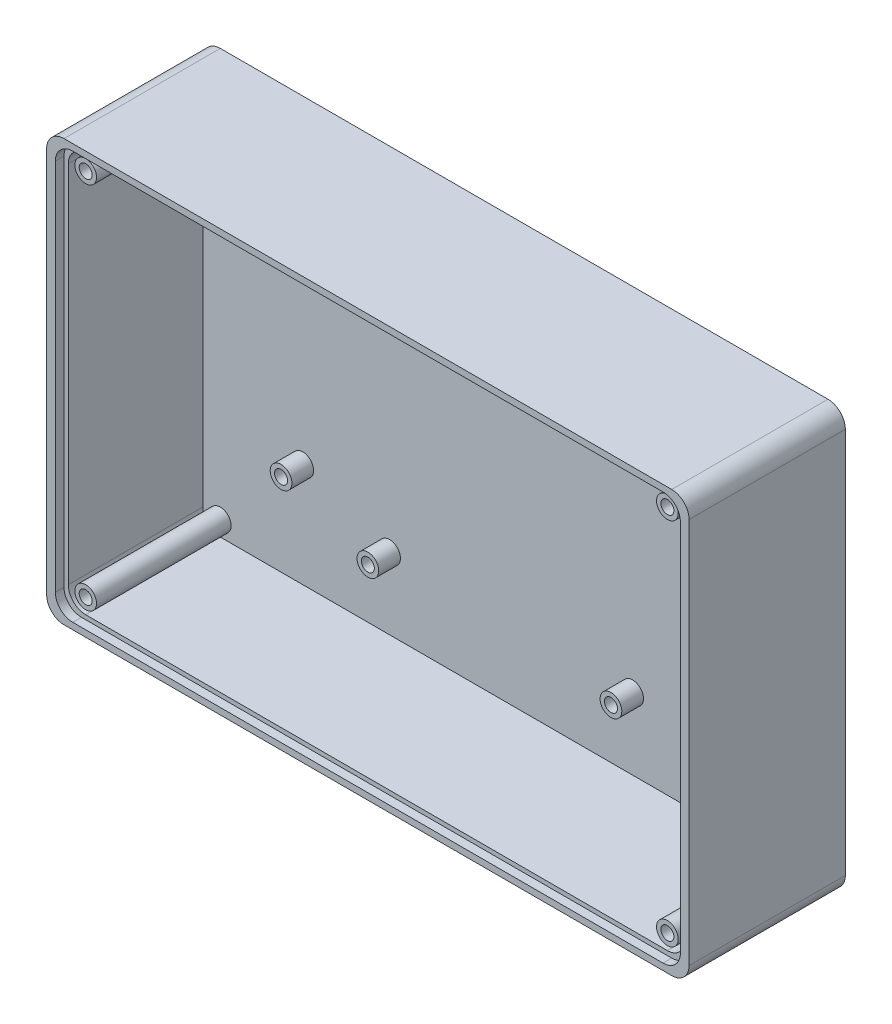
SolidWorks part; units mm, degrees
material "ABS"
ref_plane "Plano frontal" through (0, 0, 0) normal (0, 0, 1) x (1, 0, 0)
ref_plane "Plano superior" through (0, 0, 0) normal (0, 1, 0) x (1, 0, 0)
ref_plane "Plano direito" through (0, 0, 0) normal (1, 0, 0) x (0, 0, -1)
sketch "Esboço1" plane through (0, 0, 0) normal (0, 0, 1) x (1, 0, 0)
  line L1 (-70, -48.5) -> (70, -48.5)
  line L2 (-74, -44.5) -> (-74, 44.5)
  line L3 (-70, 48.5) -> (70, 48.5)
  line L4 (74, -44.5) -> (74, 44.5)
  line L5 (-74, -48.5) -> (74, 48.5) construction
  line L6 (-74, 48.5) -> (74, -48.5) construction
  arc A0 (70, -48.5) -> (74, -44.5) centre (70, -44.5) ccw
  arc A1 (70, 48.5) -> (74, 44.5) centre (70, 44.5) cw
  arc A2 (-74, 44.5) -> (-70, 48.5) centre (-70, 44.5) cw
  arc A3 (-70, -48.5) -> (-74, -44.5) centre (-70, -44.5) cw
  point P0 (0, 0)
  dimension "D3" = 4
  dimension "D1" = 148
  dimension "D2" = 97
extrude "Ressalto-extrusão1" add sketch "Esboço1" along normal mid plane 36
sketch "Esboço2" plane through (0, 0, 18) normal (0, 0, 1) x (1, 0, 0)
  line L1 (-68, -47) -> (68, -47)
  line L2 (-72, -43) -> (-72, 43)
  line L3 (-68, 47) -> (68, 47)
  line L4 (72, -43) -> (72, 43)
  line L5 (-72, -47) -> (72, 47) construction
  line L6 (-72, 47) -> (72, -47) construction
  arc A0 (68, 47) -> (72, 43) centre (68, 43) cw
  arc A1 (68, -47) -> (72, -43) centre (68, -43) ccw
  arc A2 (-68, -47) -> (-72, -43) centre (-68, -43) cw
  arc A3 (-72, 43) -> (-68, 47) centre (-68, 43) cw
  point P0 (0, 0)
  dimension "D3" = 4
  dimension "D1" = 94
  dimension "D2" = 144
extrude "Corte-extrusão1" cut sketch "Esboço2" against normal blind 2
sketch "Esboço3" plane through (0, 0, 16) normal (0, 0, 1) x (1, 0, 0)
  line L1 (-67, -46) -> (67, -46)
  line L2 (-71, -42) -> (-71, 42)
  line L3 (-67, 46) -> (67, 46)
  line L4 (71, -42) -> (71, 42)
  line L5 (-71, -46) -> (71, 46) construction
  line L6 (-71, 46) -> (71, -46) construction
  arc A0 (67, 46) -> (71, 42) centre (67, 42) cw
  arc A1 (67, -46) -> (71, -42) centre (67, -42) ccw
  arc A2 (-67, -46) -> (-71, -42) centre (-67, -42) cw
  arc A3 (-71, 42) -> (-67, 46) centre (-67, 42) cw
  point P0 (0, 0)
  dimension "D3" = 4
  dimension "D1" = 92
  dimension "D2" = 142
extrude "Corte-extrusão2" cut sketch "Esboço3" against normal blind 31
sketch "Esboço4" plane through (0, 0, -15) normal (0, 0, 1) x (1, 0, 0)
  line L0 (0, 0) -> (0, 58.4617) construction
  line L1 (0, 0) -> (89.051, 0) construction
  circle A0 centre (-28, 29.5) radius 1.5
  circle A1 centre (28, 29.5) radius 1.5
  circle A2 centre (-28, -29.5) radius 1.5
  circle A3 centre (28, -29.5) radius 1.5
  circle A4 centre (-28, 29.5) radius 2.5
  circle A5 centre (28, 29.5) radius 2.5
  circle A6 centre (28, -29.5) radius 2.5
  circle A7 centre (-28, -29.5) radius 2.5
  circle A8 centre (-48, 22) radius 1.5
  circle A9 centre (-48, -22) radius 1.5
  circle A10 centre (48, -22) radius 1.5
  circle A11 centre (48, 22) radius 1.5
  circle A12 centre (-48, 22) radius 2.5
  circle A13 centre (-48, -22) radius 2.5
  circle A14 centre (48, -22) radius 2.5
  circle A15 centre (48, 22) radius 2.5
  dimension "D1" = 59
  dimension "D2" = 56
  dimension "D3" = 3
  dimension "D4" = 5
  dimension "D5" = 44
  dimension "D6" = 96
extrude "Ressalto-extrusão2" add sketch "Esboço4" along normal blind 5
sketch "Esboço5" plane through (0, 0, -15) normal (0, 0, 1) x (1, 0, 0)
  line L0 (0, 0) -> (0, 70.3213) construction
  line L1 (0, 0) -> (106.1724, 0) construction
  circle A0 centre (-67, 42.5) radius 1.5
  circle A1 centre (67, 42.5) radius 1.5
  circle A2 centre (-67, -42.5) radius 1.5
  circle A3 centre (67, -42.5) radius 1.5
  circle A4 centre (-48, -22) radius 1.5 construction
  circle A5 centre (-67, -42.5) radius 2.5
  circle A6 centre (67, -42.5) radius 2.5
  circle A7 centre (67, 42.5) radius 2.5
  circle A8 centre (-67, 42.5) radius 2.5
  circle A9 centre (-48, 22) radius 2.5 construction
  dimension "D1" = 134
  dimension "D2" = 85
extrude "Ressalto-extrusão3" add sketch "Esboço5" along normal up to surface (31 mm away) up to face at (0, 0, 16)
